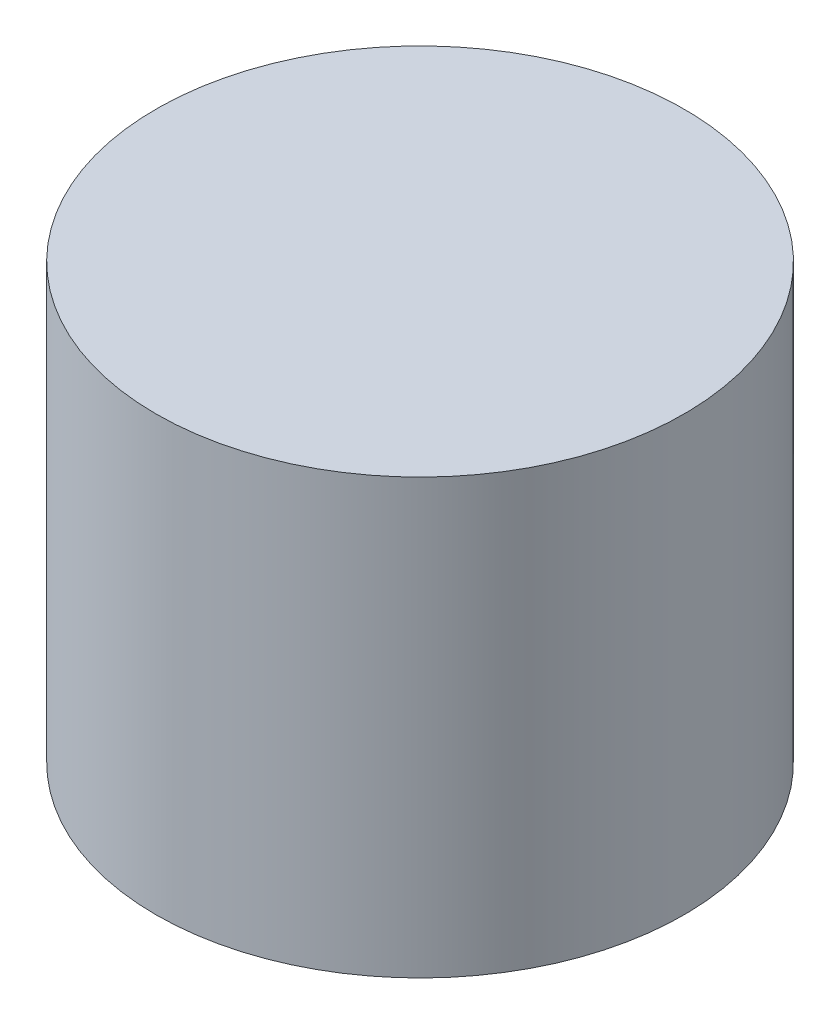
SolidWorks part; units mm, degrees
ref_plane "Front" through (0, 0, 0) normal (0, 0, 1) x (1, 0, 0)
ref_plane "Top" through (0, 0, 0) normal (0, 1, 0) x (1, 0, 0)
ref_plane "Right" through (0, 0, 0) normal (1, 0, 0) x (0, 0, -1)
sketch "Эскиз1" plane through (0, 0, 0) normal (0, 1, 0) x (1, 0, 0)
  circle A0 centre (0, 0) radius 2.8
  dimension "D1" = 5.6
extrude "Бобышка-Вытянуть1" add sketch "Эскиз1" along normal blind 4.6
